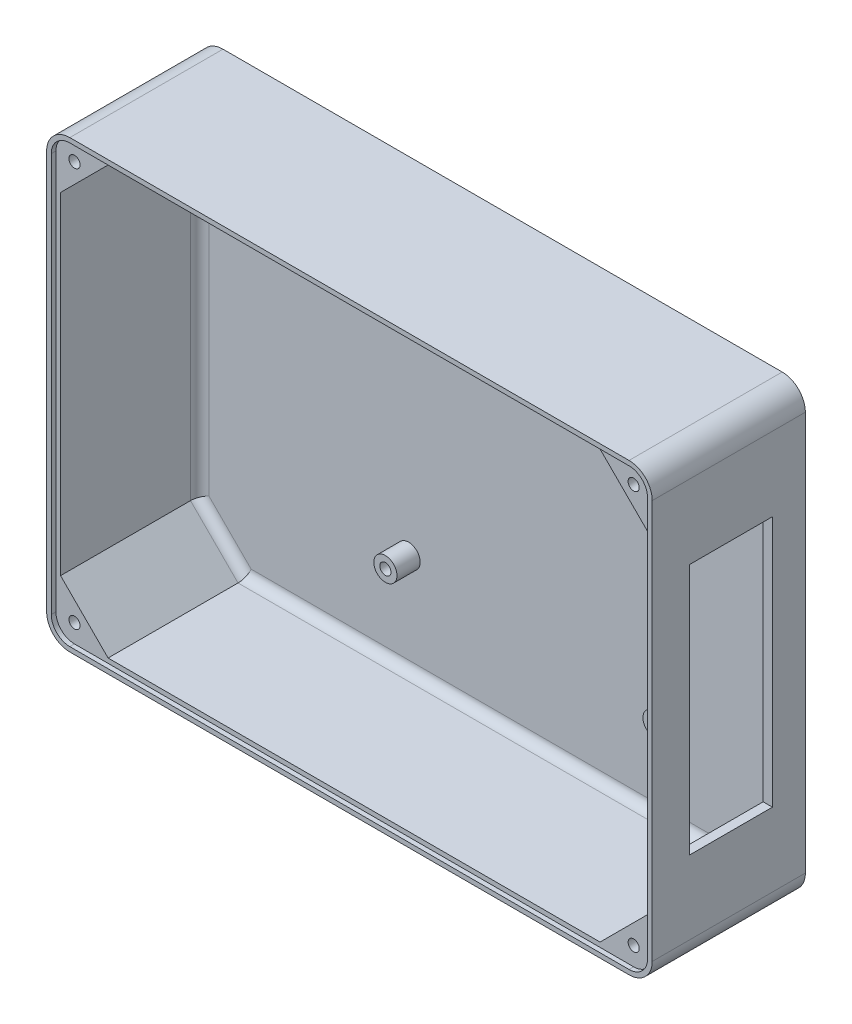
SolidWorks part; units mm, degrees
ref_plane "Front Plane" through (0, 0, 0) normal (0, 0, 1) x (1, 0, 0)
ref_plane "Top Plane" through (0, 0, 0) normal (0, 1, 0) x (1, 0, 0)
ref_plane "Right Plane" through (0, 0, 0) normal (1, 0, 0) x (0, 0, -1)
sketch "Sketch1" plane through (0, 0, -5) normal (0, 0, -1) x (-1, 0, 0)
  line L8 (77.1004, -47.0517) -> (197.5995, -47.0517)
  line L9 (72.1004, 43.9483) -> (72.1004, -42.0517)
  line L10 (197.5995, 48.9483) -> (77.1004, 48.9483)
  line L11 (202.5995, -42.0517) -> (202.5995, 43.9483)
  line L12 (77.1004, -47.0517) -> (197.5995, -47.0517)
  line L13 (72.1004, 43.9483) -> (72.1004, -42.0517)
  line L14 (197.5995, 48.9483) -> (77.1004, 48.9483)
  line L15 (202.5995, -42.0517) -> (202.5995, 43.9483)
  arc A8 (72.1004, -42.0517) -> (77.1004, -47.0517) centre (77.1004, -42.0517) ccw
  arc A9 (77.1004, 48.9483) -> (72.1004, 43.9483) centre (77.1004, 43.9483) ccw
  arc A10 (202.5995, 43.9483) -> (197.5995, 48.9483) centre (197.5995, 43.9483) ccw
  arc A11 (197.5995, -47.0517) -> (202.5995, -42.0517) centre (197.5995, -42.0517) ccw
  arc A12 (72.1004, -42.0517) -> (77.1004, -47.0517) centre (77.1004, -42.0517) ccw
  arc A13 (77.1004, 48.9483) -> (72.1004, 43.9483) centre (77.1004, 43.9483) ccw
  arc A14 (202.5995, 43.9483) -> (197.5995, 48.9483) centre (197.5995, 43.9483) ccw
  arc A15 (197.5995, -47.0517) -> (202.5995, -42.0517) centre (197.5995, -42.0517) ccw
  dimension "D1" = 0
extrude "Boss-Extrude1" add sketch "Sketch1" along normal blind 2
sketch "Sketch2" plane through (0, 0, -5) normal (0, 0, 1) x (1, 0, 0)
  line L8 (-197.5995, -47.0517) -> (-77.1004, -47.0517)
  line L9 (-72.1004, -42.0517) -> (-72.1004, 43.9483)
  line L10 (-77.1004, 48.9483) -> (-197.5995, 48.9483)
  line L11 (-202.5995, 43.9483) -> (-202.5995, -42.0517)
  line L16 (-74.1004, -42.0517) -> (-74.1004, 43.9483)
  line L17 (-77.1004, 46.9483) -> (-197.5995, 46.9483)
  line L18 (-200.5995, 43.9483) -> (-200.5995, -42.0517)
  line L19 (-197.5995, -45.0517) -> (-77.1004, -45.0517)
  line L20 (-200.5995, -34.809) -> (-190.3569, -45.0517)
  line L21 (-74.1004, -34.809) -> (-84.3431, -45.0517)
  line L22 (-200.5995, 36.7057) -> (-190.3569, 46.9483)
  line L23 (-74.1004, 36.7057) -> (-84.3431, 46.9483)
  circle A2 centre (-77.1004, -42.0517) radius 3
  arc A8 (-77.1004, -47.0517) -> (-72.1004, -42.0517) centre (-77.1004, -42.0517) ccw
  arc A9 (-72.1004, 43.9483) -> (-77.1004, 48.9483) centre (-77.1004, 43.9483) ccw
  arc A10 (-197.5995, 48.9483) -> (-202.5995, 43.9483) centre (-197.5995, 43.9483) ccw
  arc A11 (-202.5995, -42.0517) -> (-197.5995, -47.0517) centre (-197.5995, -42.0517) ccw
  arc A18 (-74.1004, 43.9483) -> (-77.1004, 46.9483) centre (-77.1004, 43.9483) ccw
  arc A19 (-197.5995, 46.9483) -> (-200.5995, 43.9483) centre (-197.5995, 43.9483) ccw
  arc A20 (-200.5995, -42.0517) -> (-197.5995, -45.0517) centre (-197.5995, -42.0517) ccw
  arc A21 (-77.1004, -45.0517) -> (-74.1004, -42.0517) centre (-77.1004, -42.0517) ccw
  arc M18 (-202.5995, -42.0517) -> (-197.5995, -47.0517) centre (-197.5995, -42.0517) ccw
  line M19 (-197.5995, -47.0517) -> (-77.1004, -47.0517)
  arc M20 (-77.1004, -47.0517) -> (-72.1004, -42.0517) centre (-77.1004, -42.0517) ccw
  line M21 (-72.1004, -42.0517) -> (-72.1004, 43.9483)
  arc M22 (-72.1004, 43.9483) -> (-77.1004, 48.9483) centre (-77.1004, 43.9483) ccw
  line M23 (-77.1004, 48.9483) -> (-197.5995, 48.9483)
  arc M24 (-197.5995, 48.9483) -> (-202.5995, 43.9483) centre (-197.5995, 43.9483) ccw
  line M25 (-202.5995, 43.9483) -> (-202.5995, -42.0517)
extrude "Boss-Extrude2" add sketch "Sketch2" along normal blind 30 contours A20 L18 A19 L17 A18 L16 A2 L19 M25 M18 M19 M20 M21 M22 M23 M24 | L18 A20 L19 L20 | L17 A19 L18 L22 | L16 A18 L17 L23 | A2 L16 L21 | A2 | A2 L21 L19
sketch "Sketch3" plane through (0, 0, 25) normal (0, 0, 1) x (1, 0, 0)
  line L0 (-137.35, -47.0517) -> (-137.35, 48.9483) construction
  line L1 (-197.5995, -47.0517) -> (-77.1004, -47.0517) construction
  line L2 (-77.1004, 48.9483) -> (-197.5995, 48.9483) construction
  line L3 (-202.5995, 0.9483) -> (-72.1004, 0.9483) construction
  line L4 (-202.5995, 43.9483) -> (-202.5995, -42.0517) construction
  line L5 (-72.1004, -42.0517) -> (-72.1004, 43.9483) construction
  circle A0 centre (-197.5995, -42.0517) radius 1.2
  circle A1 centre (-77.1004, -42.0517) radius 1.2
  circle A2 centre (-197.5995, 43.9483) radius 1.2
  circle A3 centre (-77.1004, 43.9483) radius 1.2
extrude "Cut-Extrude1" cut sketch "Sketch3" against normal blind 25
sketch "Sketch4" plane through (0, 0, 25) normal (0, 0, 1) x (1, 0, 0)
  line L0 (-201.5995, 43.9483) -> (-201.5995, -42.0517)
  line L1 (-197.5995, -46.0517) -> (-77.1004, -46.0517)
  line L2 (-73.1004, -42.0517) -> (-73.1004, 43.9483)
  line L3 (-77.1004, 47.9483) -> (-197.5995, 47.9483)
  line L4 (-202.5995, 43.9483) -> (-202.5995, -42.0517)
  line L5 (-197.5995, -47.0517) -> (-77.1004, -47.0517)
  line L6 (-72.1004, -42.0517) -> (-72.1004, 43.9483)
  line L7 (-77.1004, 48.9483) -> (-197.5995, 48.9483)
  line L8 (-202.5995, 43.9483) -> (-202.5995, -42.0517)
  line L9 (-197.5995, -47.0517) -> (-77.1004, -47.0517)
  line L10 (-72.1004, -42.0517) -> (-72.1004, 43.9483)
  line L11 (-77.1004, 48.9483) -> (-197.5995, 48.9483)
  arc A0 (-201.5995, -42.0517) -> (-197.5995, -46.0517) centre (-197.5995, -42.0517) ccw
  arc A1 (-77.1004, -46.0517) -> (-73.1004, -42.0517) centre (-77.1004, -42.0517) ccw
  arc A2 (-73.1004, 43.9483) -> (-77.1004, 47.9483) centre (-77.1004, 43.9483) ccw
  arc A3 (-197.5995, 47.9483) -> (-201.5995, 43.9483) centre (-197.5995, 43.9483) ccw
  arc A4 (-202.5995, -42.0517) -> (-197.5995, -47.0517) centre (-197.5995, -42.0517) ccw
  arc A5 (-77.1004, -47.0517) -> (-72.1004, -42.0517) centre (-77.1004, -42.0517) ccw
  arc A6 (-72.1004, 43.9483) -> (-77.1004, 48.9483) centre (-77.1004, 43.9483) ccw
  arc A7 (-197.5995, 48.9483) -> (-202.5995, 43.9483) centre (-197.5995, 43.9483) ccw
  arc A8 (-202.5995, -42.0517) -> (-197.5995, -47.0517) centre (-197.5995, -42.0517) ccw
  arc A9 (-77.1004, -47.0517) -> (-72.1004, -42.0517) centre (-77.1004, -42.0517) ccw
  arc A10 (-72.1004, 43.9483) -> (-77.1004, 48.9483) centre (-77.1004, 43.9483) ccw
  arc A11 (-197.5995, 48.9483) -> (-202.5995, 43.9483) centre (-197.5995, 43.9483) ccw
  dimension "D1" = 0
  dimension "D2" = 1
extrude "Boss-Extrude3" add sketch "Sketch4" along normal blind 1
sketch "Sketch6" plane through (-72.1004, 0, 0) normal (1, 0, 0) x (0, 0, -1)
  line L0 (-15.93, 26.4955) -> (-10.73, 26.4955) construction
  line L1 (-16.43, 13.8955) -> (-16.43, 25.9955) construction
  line L2 (-10.73, 26.4955) -> (-10.73, 26.0955) construction
  line L3 (-10.73, 26.195) -> (-10.73, 26.4955) construction
  line L4 (-1.6, -8.8294) -> (-1.73, -8.8294) construction
  line L5 (-15.1, -24.7094) -> (-1.6, -24.7094) construction
  line L6 (-15.1, -8.8294) -> (-15.1, -24.7094) construction
  line L7 (-16.93, -8.8294) -> (-15.1, -8.8294) construction
  line L8 (-16.93, -8.8294) -> (-16.93, 26.9955) construction
  line L9 (-10.73, 13.3955) -> (-10.73, 13.6955) construction
  line L10 (-10.73, 13.7937) -> (-10.73, 13.3955) construction
  line L11 (-10.73, -4.2193) -> (-10.73, 8.0825) construction
  line L12 (-10.73, -4.6175) -> (-10.73, -4.3175) construction
  line L13 (-10.73, 8.4825) -> (-10.73, -4.6175) construction
  line L14 (-10.73, 8.182) -> (-10.73, 8.4825) construction
  line L15 (-2.23, 26.4955) -> (-2.23, 13.3955) construction
  line L16 (-16.43, -4.1175) -> (-16.43, 7.9825) construction
  line L17 (-17.93, -26.2094) -> (-0.1, -26.2094) construction
  line L18 (-0.1, -26.2094) -> (-0.1, 27.9955) construction
  line L19 (-17.93, 27.9955) -> (-0.1, 27.9955) construction
  line L20 (-17.93, -26.2094) -> (-17.93, 27.9955) construction
  line L21 (-15.93, 26.4955) -> (-10.73, 26.4955)
  line L22 (-16.43, 13.8955) -> (-16.43, 25.9955)
  line L23 (-10.73, 26.4955) -> (-10.73, 26.0955)
  line L24 (-10.73, 26.195) -> (-10.73, 26.4955)
  line L25 (-1.6, -8.8294) -> (-1.73, -8.8294)
  line L26 (-15.1, -24.7094) -> (-1.6, -24.7094)
  line L27 (-15.1, -8.8294) -> (-15.1, -24.7094)
  line L28 (-16.93, -8.8294) -> (-15.1, -8.8294)
  line L29 (-16.93, -8.8294) -> (-16.93, 26.9955)
  line L30 (-10.73, 13.3955) -> (-10.73, 13.6955)
  line L31 (-10.73, 13.7937) -> (-10.73, 13.3955)
  line L32 (-10.73, -4.2193) -> (-10.73, 8.0825)
  line L33 (-10.73, -4.6175) -> (-10.73, -4.3175)
  line L34 (-10.73, 8.4825) -> (-10.73, -4.6175)
  line L35 (-10.73, 8.182) -> (-10.73, 8.4825)
  line L36 (-2.23, 26.4955) -> (-2.23, 13.3955)
  line L37 (-16.43, -4.1175) -> (-16.43, 7.9825)
  line L38 (-17.93, -26.2094) -> (-0.1, -26.2094)
  line L39 (-0.1, -26.2094) -> (-0.1, 27.9955)
  line L40 (-17.93, 27.9955) -> (-0.1, 27.9955)
  line L41 (-17.93, -26.2094) -> (-17.93, 27.9955)
  arc A0 (-7.8885, 26.195) -> (-7.9199, 26.0955) centre (-7.43, 25.9955) ccw construction
  arc A1 (-15.93, 26.4955) -> (-16.43, 25.9955) centre (-15.93, 25.9955) ccw construction
  arc A2 (-16.43, 13.8955) -> (-15.93, 13.3955) centre (-15.93, 13.8955) ccw construction
  arc A3 (-7.8885, 8.182) -> (-7.9199, 8.0825) centre (-7.43, 7.9825) ccw construction
  arc A4 (-7.9195, 13.7937) -> (-7.8883, 13.6955) centre (-7.43, 13.8955) ccw construction
  arc A5 (-15.93, 8.4825) -> (-16.43, 7.9825) centre (-15.93, 7.9825) ccw construction
  arc A6 (-16.43, -4.1175) -> (-15.93, -4.6175) centre (-15.93, -4.1175) ccw construction
  arc A7 (-7.9195, -4.2193) -> (-7.8883, -4.3175) centre (-7.43, -4.1175) ccw construction
  arc A8 (-7.8885, 26.195) -> (-7.9199, 26.0955) centre (-7.43, 25.9955) ccw
  arc A9 (-15.93, 26.4955) -> (-16.43, 25.9955) centre (-15.93, 25.9955) ccw
  arc A10 (-16.43, 13.8955) -> (-15.93, 13.3955) centre (-15.93, 13.8955) ccw
  arc A11 (-7.8885, 8.182) -> (-7.9199, 8.0825) centre (-7.43, 7.9825) ccw
  arc A12 (-7.9195, 13.7937) -> (-7.8883, 13.6955) centre (-7.43, 13.8955) ccw
  arc A13 (-15.93, 8.4825) -> (-16.43, 7.9825) centre (-15.93, 7.9825) ccw
  arc A14 (-16.43, -4.1175) -> (-15.93, -4.6175) centre (-15.93, -4.1175) ccw
  arc A15 (-7.9195, -4.2193) -> (-7.8883, -4.3175) centre (-7.43, -4.1175) ccw
extrude "Cut-Extrude2" cut sketch "Sketch6" against normal blind 2
sketch "Sketch7" plane through (0, 0, -5) normal (0, 0, 1) x (1, 0, 0)
  circle A0 centre (-155.6004, -23.5517) radius 2.5
  circle A1 centre (-155.6004, -23.5517) radius 1.375
  circle A2 centre (-155.6004, -23.5517) radius 1.375
  circle A3 centre (-155.6004, 25.4483) radius 1.375
  circle A4 centre (-155.6004, 25.4483) radius 1.375
  circle A5 centre (-97.6004, 25.4483) radius 1.375
  circle A6 centre (-97.6004, 25.4483) radius 1.375
  circle A7 centre (-97.6004, -23.5517) radius 1.375
  circle A8 centre (-97.6004, -23.5517) radius 1.375
  circle A9 centre (-97.6004, -23.5517) radius 2.5
  circle A10 centre (-97.6004, 25.4483) radius 2.5
  circle A11 centre (-155.6004, 25.4483) radius 2.5
  circle A12 centre (-155.6004, -23.5517) radius 1.2
  circle A13 centre (-155.6004, 25.4483) radius 1.2
  circle A14 centre (-97.6004, 25.4483) radius 1.2
  circle A15 centre (-97.6004, -23.5517) radius 1.2
  dimension "D1" = 0
  dimension "D2" = 0
  dimension "D3" = 0
  dimension "D4" = 0
extrude "Boss-Extrude4" add sketch "Sketch7" along normal blind 5 contours A0 A2 | A2 A12 | A11 A4 | A4 A13 | A6 A14 | A10 A6 | A8 A15 | A9 A8
fillet "Fillet1" radius 2 8 edges at (-195.4782, -39.9304, -5) (-137.35, -45.0517, -5) (-79.2218, -39.9304, -5) (-74.1004, 0.9483, -5) (-79.2218, 41.827, -5) (-200.5995, 0.9483, -5) (-195.4782, 41.827, -5) (-137.35, 46.9483, -5)
